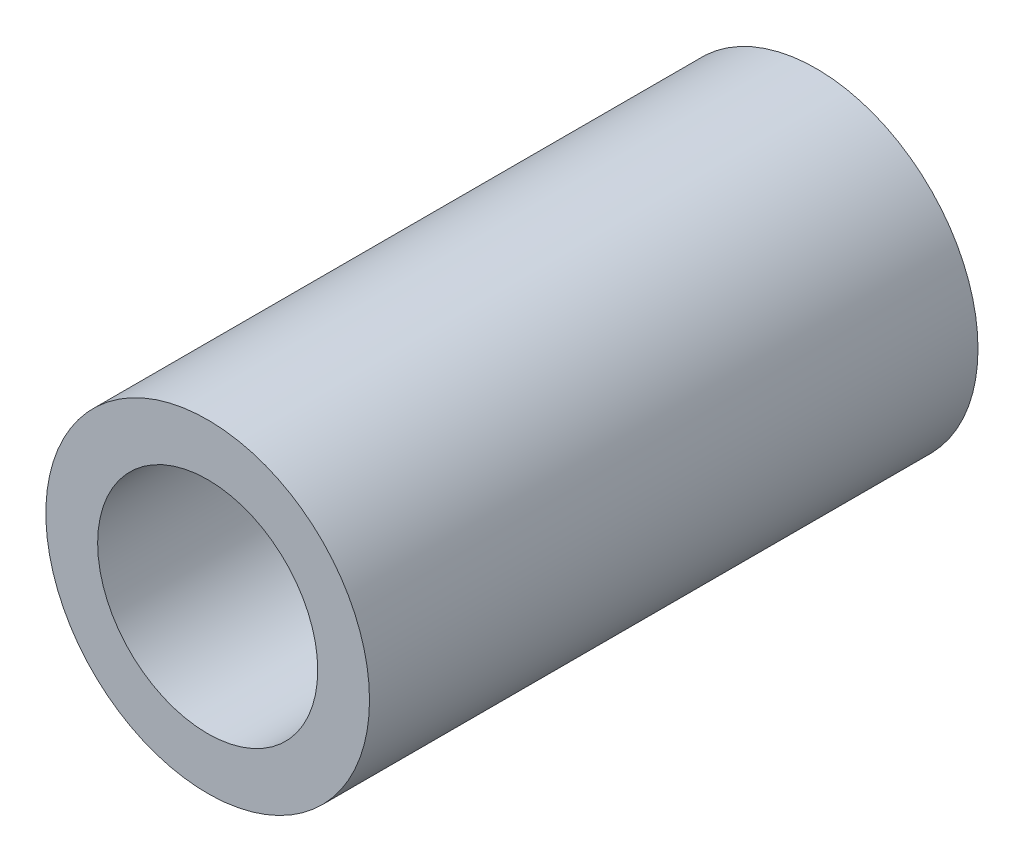
SolidWorks part; units mm, degrees
ref_plane "Front Plane" through (0, 0, 0) normal (1, 0, 0) x (0, 1, 0)
ref_plane "Top Plane" through (0, 0, 0) normal (0, 0, 1) x (0, 1, 0)
ref_plane "Right Plane" through (0, 0, 0) normal (0, 1, 0) x (-1, 0, 0)
sketch "Sketch1" plane through (0, 0, 0) normal (0, 0, 1) x (0, 1, 0)
  circle A0 centre (0, 0) radius 2.5
  dimension "D1" = 5
extrude "Boss-Extrude1" add sketch "Sketch1" along normal blind 9.4
sketch "Sketch2" plane through (0, 0, 9.4) normal (0, 0, 1) x (1, 0, 0)
  circle A0 centre (0, 0) radius 1.7
  dimension "D1" = 3.4
extrude "Cut-Extrude1" cut sketch "Sketch2" against normal through all both and the other way through all
